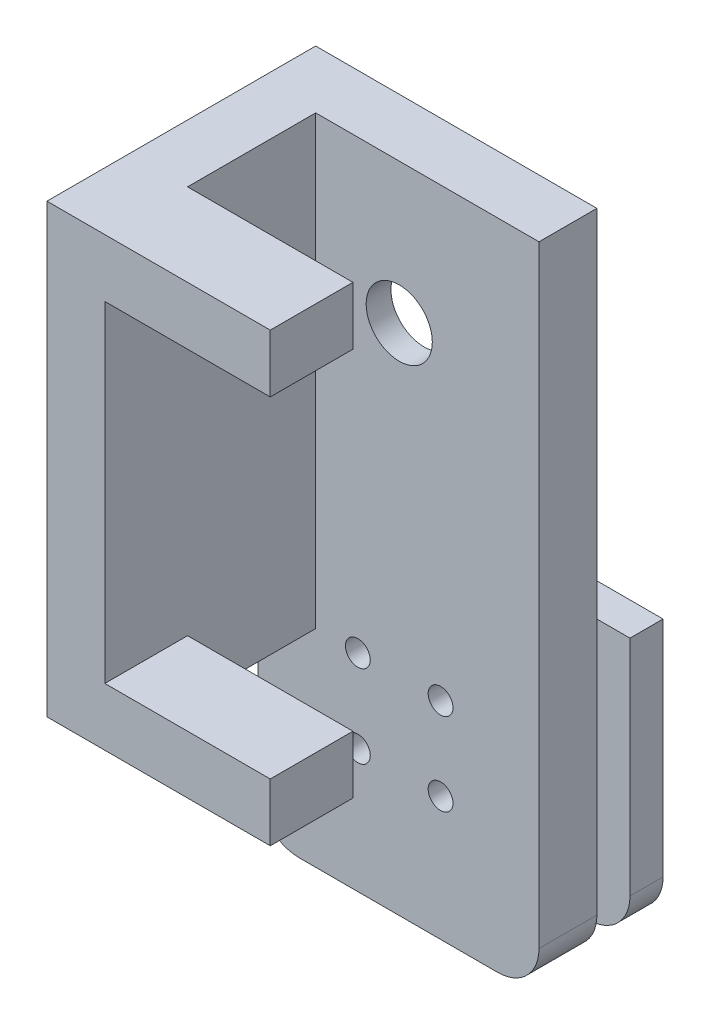
SolidWorks part; units mm, degrees
ref_plane "Front Plane" through (0, 0, 0) normal (0, 0, 1) x (1, 0, 0)
ref_plane "Top Plane" through (0, 0, 0) normal (0, 1, 0) x (1, 0, 0)
ref_plane "Right Plane" through (0, 0, 0) normal (1, 0, 0) x (0, 0, -1)
sketch "Sketch1" plane through (0, 0, 0) normal (0, 0, 1) x (1, 0, 0)
  line L1 (0, 0) -> (27, 0)
  line L2 (0, 0) -> (0, 54)
  line L3 (0, 54) -> (27, 54)
  line L4 (7, 7) -> (7, 47)
  line L5 (27, 54) -> (27, 47)
  line L6 (27, 47) -> (7, 47)
  line L8 (27, 0) -> (27, 7)
  line L9 (27, 7) -> (7, 7)
  dimension "D1" = 40
  dimension "D2" = 7
  dimension "D3" = 20
  dimension "D4" = 7
extrude "Boss-Extrude1" add sketch "Sketch1" along normal blind 10
sketch "Sketch2" plane through (0, 0, 0) normal (0, 0, -1) x (-1, 0, 0)
  line L1 (0, 54) -> (0, 0) construction
  line L2 (0, 54) -> (0, 0)
  line L9 (0, 0) -> (-27, 0) construction
  line L10 (-7, 0) -> (0, 0)
  line L11 (-7, 0) -> (-7, 54)
  line L12 (-27, 54) -> (0, 54) construction
  line L13 (-7, 7) -> (-7, 47) construction
  line L14 (-7, 54) -> (0, 54)
extrude "Boss-Extrude2" add sketch "Sketch2" along normal blind 15.494
sketch "Sketch3" plane through (0, 0, 0) normal (-1, 0, 0) x (0, 0, 1)
  line L0 (10, 0) -> (-15.494, 0) construction
  line L3 (-15.494, 0) -> (-22.494, 0)
  line L4 (-22.494, 54) -> (-22.494, 0)
  line L6 (-15.494, 0) -> (-15.494, 54)
  line L7 (-15.494, 54) -> (-22.494, 54)
  dimension "D1" = 7
extrude "Boss-Extrude3" add sketch "Sketch3" against normal blind 34
sketch "Sketch5" plane through (0, 0, -22.494) normal (0, 0, -1) x (-1, 0, 0)
  line L1 (-34, 0) -> (-34, 54) construction
  line L2 (-34, 54) -> (0, 54) construction
  circle A1 centre (-17.1, 37.04) radius 11
  dimension "D1" = 22
  dimension "D2" = 16.96
  dimension "D3" = 16.9
extrude "Cut-Extrude2" cut sketch "Sketch5" against normal blind 4
sketch "Sketch6" plane through (0, 0, -18.494) normal (0, 0, -1) x (-1, 0, 0)
  circle A0 centre (-17.1, 37.04) radius 4
  circle A1 centre (-17.1, 37.04) radius 11 construction
  dimension "D1" = 8
extrude "Cut-Extrude3" cut sketch "Sketch6" against normal blind 10
sketch "Sketch7" plane through (0, 0, 0) normal (0, -1, 0) x (1, 0, 0)
  line L0 (0, 10) -> (0, -22.494) construction
  line L1 (34, -22.494) -> (0, -22.494)
  line L2 (34, -22.494) -> (34, -15.494)
  line L3 (34, -15.494) -> (0, -15.494)
  line L4 (0, -22.494) -> (0, -15.494)
  line L5 (34, -15.494) -> (7, -15.494) construction
extrude "Boss-Extrude4" add sketch "Sketch7" along normal blind 25
sketch "Sketch8" plane through (0, -25, 0) normal (0, -1, 0) x (1, 0, 0)
  line L0 (0, -22.494) -> (0, -30.494)
  line L1 (0, -30.494) -> (34, -30.494)
  line L2 (34, -30.494) -> (34, -26.494)
  line L3 (34, -26.494) -> (7, -26.494)
  line L4 (7, -26.494) -> (7, -22.494)
  line L5 (7, -22.494) -> (0, -22.494)
  line L6 (34, -22.494) -> (34, -15.494) construction
  dimension "D1" = 4
  dimension "D2" = 4
  dimension "D3" = 7
extrude "Boss-Extrude5" add sketch "Sketch8" against normal up to surface (32 mm away) up to face at (17, 7, 5)
hole_wizard "Ø3.0mm Dowel Hole1" positions "Sketch9" profile "Sketch10" hole size "Ø3.0" standard "DIN"
sketch "Sketch9" plane through (0, 0, -30.494) normal (0, 0, -1) x (-1, 0, 0)
  line L1 (-12.1, 0) -> (-22.1, 0) construction
  line L2 (-12.1, 0) -> (-12.1, -10) construction
  line L3 (-12.1, -10) -> (-22.1, -10) construction
  line L4 (-22.1, 0) -> (-22.1, -10) construction
  line L5 (-17.1, 18.04) -> (-17.1, -38.7246) construction
  line L7 (0, -25) -> (-34, -25) construction
  point P0 (-22.1, -10)
  point P2 (-22.1, 0)
  point P4 (-12.1, 0)
  point P6 (-12.1, -10)
  point P83 (-17.1, 0)
  dimension "D1" = 10
  dimension "D2" = 15
sketch "Sketch10" plane through (22.1, -10, -30.494) normal (1, 0, 0) x (0, 1, 0)
  line L0 (0, 0) -> (0, 27.9013)
  line L1 (0, 27.9013) -> (1.5, 27)
  line L2 (1.5, 27) -> (1.5, 0)
  line L5 (1.5, 0) -> (0, 0)
  line L10 (0, 27.9013) -> (-1.5, 27) construction
  line L11 (0, -6.35) -> (0, 107.95) construction
  dimension "Hole Dia." = 3
  dimension "Hole Depth" = 27
  dimension "Drill Angle" = 118
fillet "Fillet2" radius 5 2 edges at (34, -25, -18.994) (34, -25, -28.494)
fillet "Fillet3" radius 5 1 edges at (0, -25, -22.994)
